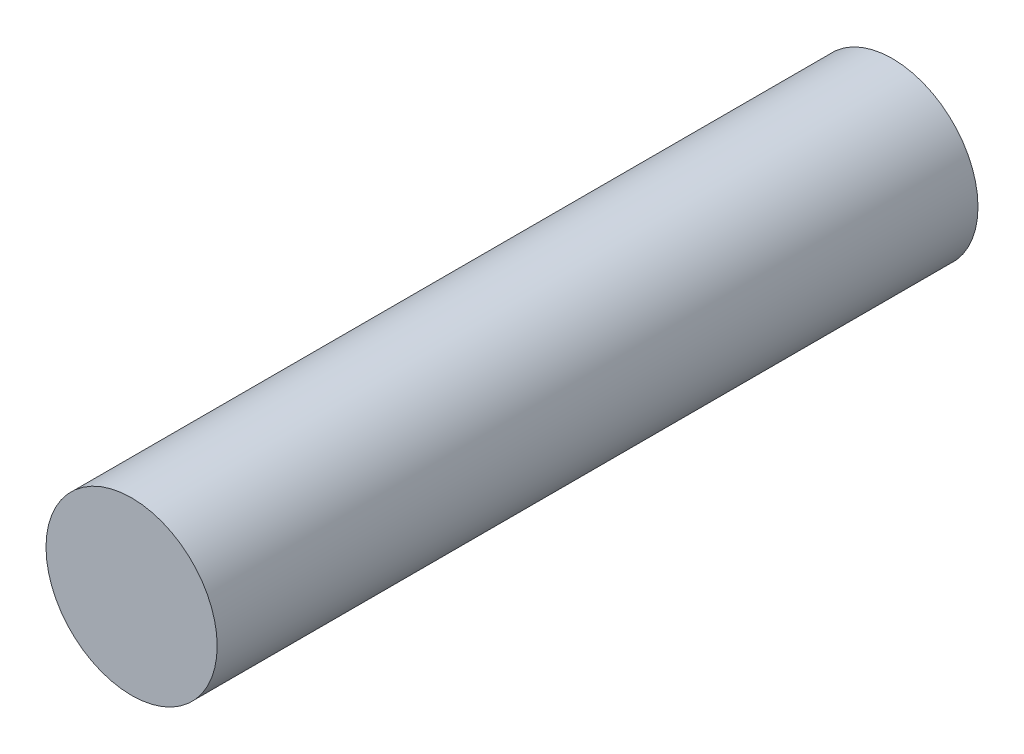
SolidWorks part; units mm, degrees
ref_plane "Front Plane" through (0, 0, 0) normal (0, 0, 1) x (1, 0, 0)
ref_plane "Top Plane" through (0, 0, 0) normal (0, 1, 0) x (1, 0, 0)
ref_plane "Right Plane" through (0, 0, 0) normal (1, 0, 0) x (0, 0, -1)
sketch "Sketch1" plane through (0, 0, 0) normal (0, 0, 1) x (1, 0, 0)
  circle A0 centre (0, 0) radius 4.5
extrude "Boss-Extrude1" add sketch "Sketch1" along normal blind 40
